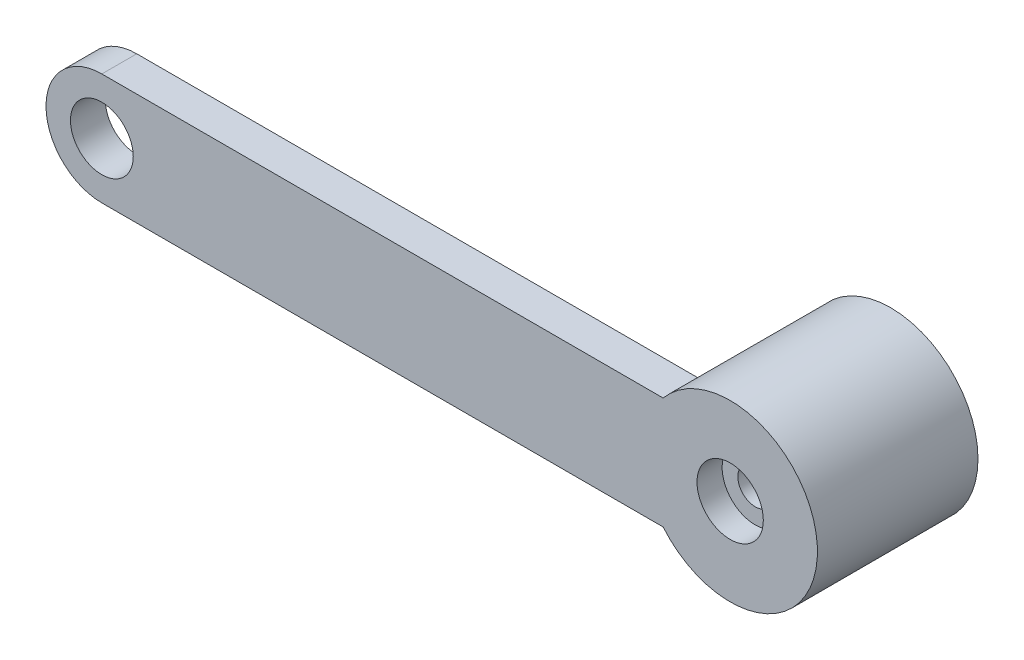
SolidWorks part; units mm, degrees
ref_plane "前视基准面" through (0, 0, 0) normal (0, 0, 1) x (1, 0, 0)
ref_plane "上视基准面" through (0, 0, 0) normal (0, 1, 0) x (1, 0, 0)
ref_plane "右视基准面" through (0, 0, 0) normal (1, 0, 0) x (0, 0, -1)
sketch "草图1" plane through (0, 0, 0) normal (0, 0, 1) x (1, 0, 0)
  line L0 (-46.4729, 0) -> (69.5255, 0) construction
  line L1 (-37.3635, 8) -> (43.0318, 8)
  line L2 (-37.3635, -8) -> (43.0318, -8)
  circle A0 centre (-37.3635, 0) radius 4.5
  arc A1 (-37.3635, 8) -> (-37.3635, -8) centre (-37.3635, 0) ccw
  arc A3 (43.0318, -8) -> (43.0318, 8) centre (52.6365, 0) ccw
  dimension "D1" = 9
  dimension "D2" = 16
  dimension "D4" = 25
  dimension "D5" = 90
extrude "凸台-拉伸1" add sketch "草图1" along normal blind 5
sketch "草图4" plane through (0, 0, 0) normal (0, 0, -1) x (-1, 0, 0)
  circle A0 centre (-52.6365, 0) radius 12.5
extrude "凸台-拉伸3" add sketch "草图4" along normal blind 18
sketch "草图5" plane through (0, 0, -18) normal (0, 0, -1) x (-1, 0, 0)
  circle A0 centre (-52.6365, 0) radius 9
  dimension "D1" = 18
extrude "切除-拉伸1" cut sketch "草图5" against normal blind 15
sketch "草图6" plane through (0, 0, 5) normal (0, 0, 1) x (1, 0, 0)
  circle A0 centre (52.6365, 0) radius 2.5
  dimension "D1" = 5
extrude "切除-拉伸2" cut sketch "草图6" against normal up to next
sketch "草图7" plane through (0, 0, 5) normal (0, 0, 1) x (1, 0, 0)
  circle A0 centre (52.6365, 0) radius 4.75
  dimension "D1" = 9.5
extrude "切除-拉伸3" cut sketch "草图7" against normal blind 3.6
